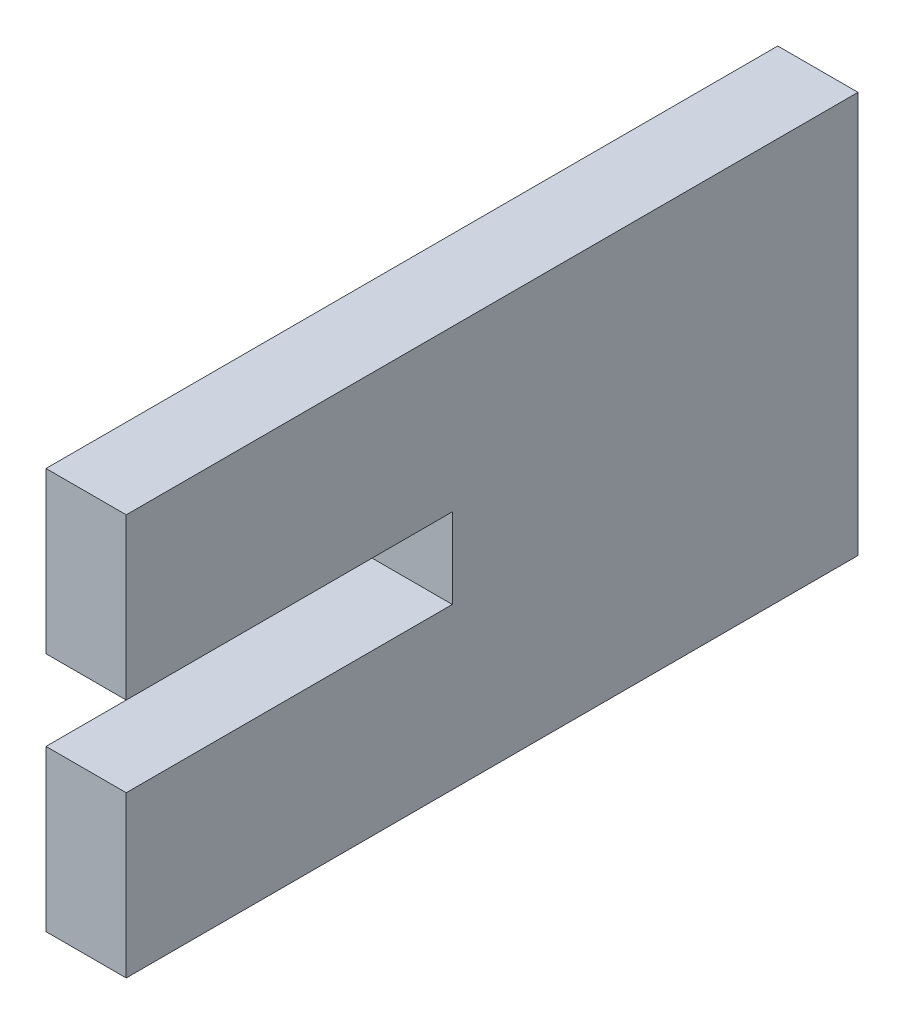
SolidWorks part; units mm, degrees
ref_plane "Front Plane" through (0, 0, 0) normal (0, 0, 1) x (1, 0, 0)
ref_plane "Top Plane" through (0, 0, 0) normal (0, 1, 0) x (1, 0, 0)
ref_plane "Right Plane" through (0, 0, 0) normal (1, 0, 0) x (0, 0, -1)
sketch "Sketch1" plane through (0, 0, 0) normal (1, 0, 0) x (0, 0, -1)
  line L0 (59.162, 20) -> (59.162, -20)
  line L1 (59.162, -20) -> (-13.8065, -20)
  line L2 (-13.8065, -20) -> (-13.8065, -4)
  line L3 (-13.8065, -4) -> (18.7097, -4)
  line L4 (18.7097, -4) -> (18.7097, 4)
  line L5 (18.7097, 4) -> (-13.8065, 4)
  line L6 (-13.8065, 4) -> (-13.8065, 20)
  line L7 (-13.8065, 20) -> (59.162, 20)
  line L8 (27.5355, 0) -> (-27.5355, 0) construction
  point P2 (59.162, 0)
  point P9 (13.7097, 0)
  point P12 (59.162, 20)
  dimension "D1" = 8
  dimension "D2" = 40
  dimension "D3" = 5
extrude "Boss-Extrude1" add sketch "Sketch1" along normal mid plane 8
